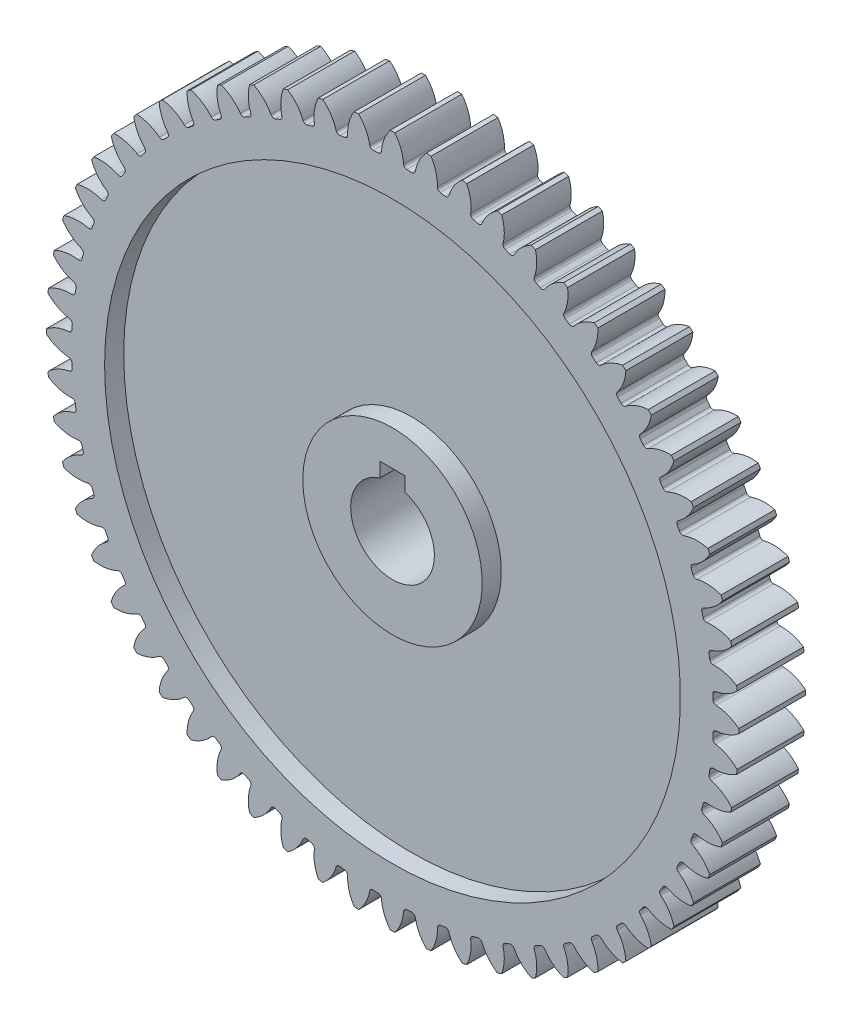
SolidWorks part; units mm, degrees
ref_plane "Front Plane" through (0, 0, 0) normal (0, 0, 1) x (1, 0, 0)
ref_plane "Top Plane" through (0, 0, 0) normal (0, 1, 0) x (1, 0, 0)
ref_plane "Right Plane" through (0, 0, 0) normal (1, 0, 0) x (0, 0, -1)
sketch "Sketch1" plane through (0, 0, 0) normal (1, 0, 0) x (0, 0, -1)
  line L0 (-7.112, 0) -> (-7.112, 32.8359)
  line L1 (-7.112, 32.8359) -> (-0.762, 32.8359)
  line L2 (-0.762, 32.8359) -> (-0.762, 8.509)
  line L3 (-0.762, 8.509) -> (7.112, 8.509)
  line L4 (7.112, 8.509) -> (7.112, 0)
  line L5 (7.112, 0) -> (-7.112, 0) construction
  line L6 (-7.112, 3.9687) -> (7.112, 3.9687)
  point P9 (-7.112, 27.305)
  dimension "OD" = 65.6717
  dimension "Face Width" = 6.35
  dimension "Hub Width" = 7.874
  dimension "Hub Diameter" = 17.018
  dimension "For Shaft Diameter" = 7.9375
  dimension "Overall Width" = 14.224
  dimension "Under Cut Diameter" = 54.61
sketch "Sketch2" plane through (0, 0, 0) normal (0, 0, 1) x (1, 0, 0)
  line L0 (-1.3192, 30.3985) -> (-0.432, 32.8359)
  line L1 (-0.432, 32.8359) -> (0.432, 32.8359)
  line L2 (0.432, 32.8359) -> (1.3192, 30.3985)
  line L3 (0, 32.8359) -> (0, 0) construction
  line L4 (0, 0) -> (-1.7185, 32.7908) construction
  line L5 (0, 0) -> (1.7185, 32.7908) construction
  line L6 (-4.4894, 30.0941) -> (-3.862, 32.6108)
  line L7 (-3.862, 32.6108) -> (-3.0026, 32.7011)
  line L8 (-3.0026, 32.7011) -> (-1.8656, 30.3698)
  line L9 (-3.4323, 32.656) -> (0, 0) construction
  line L11 (-0.432, 32.8359) -> (0, 32.8359) construction
  line L12 (-0.8312, 31.7391) -> (0.8312, 31.7391) construction
  circle A0 centre (0, 0) radius 31.75 construction
  circle A2 centre (0, 0) radius 32.8359
  circle A3 centre (0, 0) radius 30.4271
  arc A5 (-0.216, 32.8359) -> (-1.0661, 30.4084) centre (2.8289, 30.407) ccw
  arc A6 (1.0661, 30.4084) -> (0.216, 32.8359) centre (-2.8289, 30.407) ccw
  arc A7 (-2.1183, 30.3533) -> (-3.2174, 32.6786) centre (-5.9918, 29.9447) ccw
  arc A8 (-0.8312, 31.7391) -> (0.8312, 31.7391) centre (0, 0) cw
  point P3 (0, 31.75)
  point P5 (3.3188, 31.5761)
  point P6 (27.4963, -15.875)
  point P9 (6.6012, 31.0562)
  point P10 (9.8113, 30.196)
  point P11 (12.9139, 29.0051)
  point P12 (15.875, 27.4963)
  point P13 (18.6622, 25.6863)
  point P14 (21.2449, 23.5948)
  point P15 (23.5948, 21.2449)
  point P16 (25.6863, 18.6622)
  point P17 (27.4963, 15.875)
  point P18 (29.0051, 12.9139)
  point P19 (30.196, 9.8113)
  point P20 (31.0562, 6.6012)
  point P21 (31.5761, 3.3188)
  point P22 (31.75, 0)
  point P23 (31.5761, -3.3188)
  point P24 (31.0562, -6.6012)
  point P25 (30.196, -9.8113)
  point P26 (29.0051, -12.9139)
  point P27 (25.6863, -18.6622)
  point P28 (23.5948, -21.2449)
  point P29 (21.2449, -23.5948)
  point P30 (18.6622, -25.6863)
  point P31 (0, 0)
  point P55 (15.875, -27.4963)
  point P56 (12.9139, -29.0051)
  point P57 (9.8113, -30.196)
  point P58 (6.6012, -31.0562)
  point P59 (3.3188, -31.5761)
  point P61 (0, -31.75)
  point P62 (-3.3188, -31.5761)
  point P63 (-6.6012, -31.0562)
  point P64 (-9.8113, -30.196)
  point P65 (-12.9139, -29.0051)
  point P66 (-15.875, -27.4963)
  point P67 (-18.6622, -25.6863)
  point P68 (-21.2449, -23.5948)
  point P69 (-23.5948, -21.2449)
  point P70 (-25.6863, -18.6622)
  point P71 (-27.4963, -15.875)
  point P72 (-29.0051, -12.9139)
  point P73 (-30.196, -9.8113)
  point P74 (-31.0562, -6.6012)
  point P75 (-31.5761, -3.3188)
  point P76 (-31.75, 0)
  point P77 (-31.5761, 3.3188)
  point P78 (-31.0562, 6.6012)
  point P79 (-30.196, 9.8113)
  point P80 (-29.0051, 12.9139)
  point P81 (-27.4963, 15.875)
  point P82 (-25.6863, 18.6622)
  point P83 (-23.5948, 21.2449)
  point P84 (-21.2449, 23.5948)
  point P85 (-18.6622, 25.6863)
  point P86 (-15.875, 27.4963)
  point P87 (-12.9139, 29.0051)
  point P88 (-9.8113, 30.196)
  point P89 (-6.6012, 31.0562)
  point P90 (-3.3188, 31.5761)
  dimension "Gear Pitch Diameter" = 63.5
  dimension "Pressure Angle" = 20
  dimension "Addendum" = 1.0858
  dimension "Dedendum" = 1.3229
  dimension "D1" = 6
  dimension "D2" = 1.6624
  dimension "Number of Teeth" = 60
sketch "Sketch3" plane through (0, 0, 0) normal (1, 0, 0) x (0, 0, -1)
  line L0 (-7.112, 32.8359) -> (-0.762, 32.8359) construction
  line L1 (7.112, 8.509) -> (7.112, 0) construction
  line L2 (-0.762, 8.509) -> (7.112, 8.509) construction
  line L3 (-0.762, 32.8359) -> (-0.762, 8.509) construction
  line L4 (-7.112, 0) -> (-7.112, 32.8359) construction
  line L5 (-7.112, 3.9687) -> (7.112, 3.9687) construction
  line L6 (-7.112, 32.8359) -> (-0.762, 32.8359)
  line L7 (7.112, 8.509) -> (7.112, 3.9687)
  line L8 (-7.112, 8.509) -> (-5.2977, 8.509)
  line L9 (-0.762, 32.8359) -> (-0.762, 27.305)
  line L10 (-7.112, 3.9687) -> (-7.112, 8.509)
  line L11 (-7.112, 3.9687) -> (7.112, 3.9687)
  line L12 (-7.112, 27.305) -> (-5.2977, 27.305)
  line L13 (-5.2977, 27.305) -> (-5.2977, 8.509)
  line L14 (-0.762, 27.305) -> (-2.5763, 27.305)
  line L15 (-2.5763, 27.305) -> (-2.5763, 8.509)
  line L16 (-2.5763, 8.509) -> (7.112, 8.509)
  line L17 (-7.112, 27.305) -> (-7.112, 32.8359)
  dimension "D1" = 1.8143
revolve "Revolve1" add sketch "Sketch3" angle 360 about L5
sketch "Sketch4" plane through (0, 0, 7.112) normal (0, 0, 1) x (1, 0, 0)
  arc A1 (-0.216, 32.8358) -> (-1.0661, 30.4084) centre (2.8289, 30.407) ccw construction
  arc A2 (-2.1183, 30.3533) -> (-3.2174, 32.6786) centre (-5.9918, 29.9447) ccw construction
  arc A3 (-0.2166, 32.8351) -> (-1.0558, 30.6908) centre (2.8289, 30.407) ccw
  arc A4 (-2.1581, 30.633) -> (-3.2168, 32.6779) centre (-5.9918, 29.9447) ccw
  circle A5 centre (0, 0) radius 32.8359 construction
  arc A6 (-0.2166, 32.8351) -> (-3.2168, 32.6779) centre (0, 0) ccw
  circle A7 centre (0, 0) radius 30.4271 construction
  arc A8 (-1.3582, 30.3968) -> (-1.8265, 30.3722) centre (0, 0) ccw
  arc A9 (-2.1581, 30.633) -> (-1.8265, 30.3722) centre (-1.8456, 30.6891) ccw
  arc A10 (-1.3582, 30.3968) -> (-1.0558, 30.6908) centre (-1.3724, 30.7139) ccw
  dimension "D1" = 0.3175
extrude "Cut-Extrude1" cut sketch "Sketch4" against normal through all both and the other way through all
pattern_circular "CirPattern1" count 60 over 360 about axis through (0, 0, 0) along (0, 0, 1) of "Cut-Extrude1"
sketch "Sketch5" plane through (0, 0, -7.112) normal (0, 0, -1) x (-1, 0, 0)
  line L1 (-1.1906, 5.1594) -> (1.1906, 5.1594)
  line L2 (-1.1906, 5.1594) -> (-1.1906, 2.7781)
  line L3 (-1.1906, 2.7781) -> (1.1906, 2.7781)
  line L4 (1.1906, 5.1594) -> (1.1906, 2.7781)
  line L5 (-1.1906, 5.1594) -> (1.1906, 2.7781) construction
  line L6 (-1.1906, 2.7781) -> (1.1906, 5.1594) construction
  circle A0 centre (0, 0) radius 3.9687 construction
  point P0 (0, 3.9687)
  point P7 (0, 0)
  point P8 (0.1786, 3.9647)
  point P9 (0, 0)
  dimension "D1" = 2.3813
extrude "Cut-Extrude2" cut sketch "Sketch5" against normal through all
equation "\"Dedendum@Sketch2\" = 1.25 /  ( \"Number of Teeth@Sketch2\" / \"Gear Pitch Diameter@Sketch2\" ) "
equation "\"D1@Sketch2\"=360/\"Number of Teeth@Sketch2\""
equation "\"D1@Sketch4\"=.3/(\"Number of Teeth@Sketch2\"/\"Gear Pitch Diameter@Sketch2\")"
equation "\"D1@CirPattern1\"=\"Number of Teeth@Sketch2\""
equation "\"D2@Sketch2\"=1.5708/(\"Number of Teeth@Sketch2\"/\"Gear Pitch Diameter@Sketch2\")"
equation "\"D1@Sketch3\"=\"Face Width@Sketch1\"/3.5"
